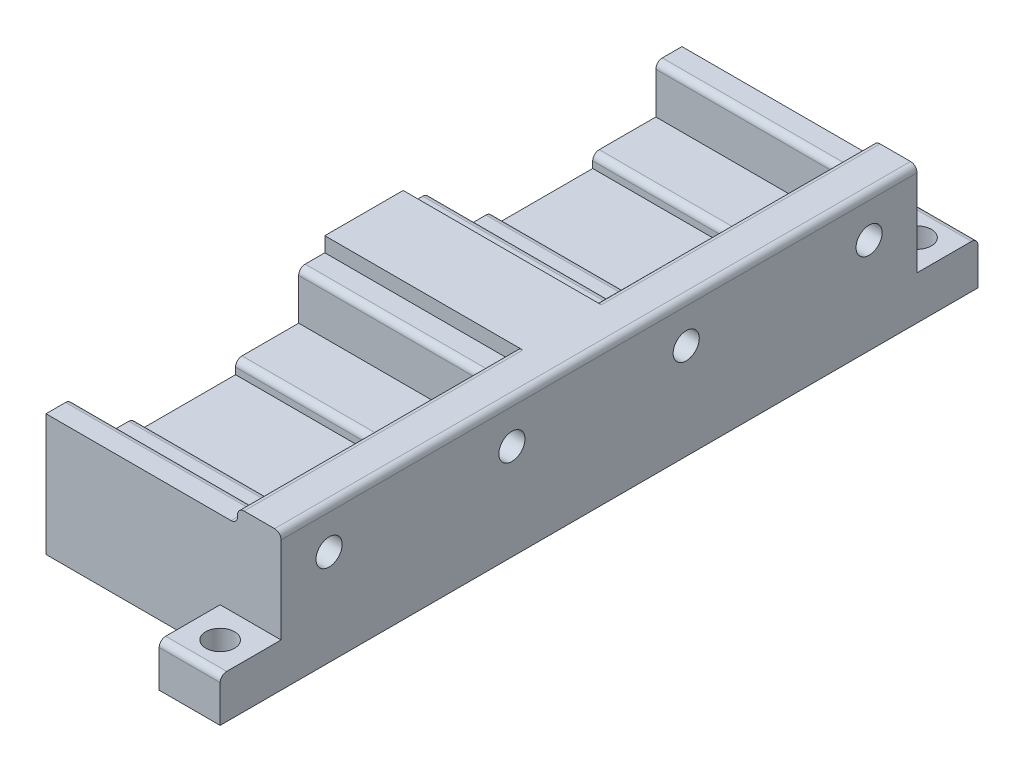
SolidWorks part; units mm, degrees
ref_plane "Front" through (0, 0, 0) normal (0, 0, 1) x (1, 0, 0)
ref_plane "Top" through (0, 0, 0) normal (0, 1, 0) x (1, 0, 0)
ref_plane "Right" through (0, 0, 0) normal (1, 0, 0) x (0, 0, -1)
sketch "Sketch1" plane through (0, 0, 0) normal (1, 0, 0) x (0, 0, -1)
  line L0 (-13.0089, 0) -> (13.0089, 0)
  line L1 (13.0089, 0) -> (13.0089, 8.5)
  line L2 (13.0089, 8.5) -> (5.7589, 8.5)
  line L3 (5.7589, 8.5) -> (5.7589, 7)
  line L4 (5.7589, 7) -> (-5.7589, 7)
  line L5 (-5.7589, 7) -> (-5.7589, 8.5)
  line L6 (-5.7589, 8.5) -> (-13.0089, 8.5)
  line L7 (-13.0089, 8.5) -> (-13.0089, 0)
  dimension "D1" = 8.5
  dimension "D2" = 7.25
  dimension "D3" = 26.0178
  dimension "D4" = 1.5
extrude "Boss-Extrude1" add sketch "Sketch1" along normal mid plane 22
sketch "Sketch3" plane through (0, 0, 0) normal (0, -1, 0) x (1, 0, 0)
  line L1 (-11, -13.0089) -> (11, -13.0089)
  line L2 (-11, -13.0089) -> (-11, -16.0089)
  line L3 (-11, -16.0089) -> (11, -16.0089)
  line L4 (11, -13.0089) -> (11, -16.0089)
  line L5 (-11, 13.0089) -> (11, 13.0089)
  line L6 (-11, 13.0089) -> (-11, 16.0089)
  line L7 (-11, 16.0089) -> (11, 16.0089)
  line L8 (11, 13.0089) -> (11, 16.0089)
  dimension "D1" = 3
  dimension "D2" = 22
  dimension "D3" = 3
  dimension "D4" = 22
extrude "Boss-Extrude2" add sketch "Sketch3" against normal blind 14
sketch "Sketch4" plane through (11, 0, 0) normal (1, 0, 0) x (0, 0, -1)
  line L0 (0, 0) -> (0, 15.7) construction
  line L1 (-16.0089, 0) -> (16.0089, 0) construction
  line L2 (-8.8, 15.7) -> (-16.0089, 15.7)
  line L3 (-16.0089, 14) -> (-16.0089, 0) construction
  line L4 (-16.0089, 15.7) -> (-16.0089, 0)
  line L5 (-16.0089, 0) -> (16.0089, 0)
  line L6 (16.0089, 0) -> (16.0089, 15.7)
  line L7 (16.0089, 14) -> (16.0089, 0) construction
  line L8 (16.0089, 15.7) -> (-8.8, 15.7)
  point P6 (0, 0)
  dimension "D2" = 15.7
extrude "Boss-Extrude3" add sketch "Sketch4" along normal blind 5
sketch "Sketch5" plane through (16, 0, 0) normal (1, 0, 0) x (0, 0, -1)
  line L0 (-16.0089, 11) -> (-10.5, 11) construction
  line L1 (-16.0089, 15.7) -> (-16.0089, 0) construction
  line L2 (-10.5, 11) -> (-10.5, 0) construction
  line L3 (-16.0089, 0) -> (16.0089, 0) construction
  line L4 (0, 0) -> (0, 15.7) construction
  line L5 (16.0089, 15.7) -> (-16.0089, 15.7) construction
  circle A0 centre (-10.5, 11) radius 1.5
  circle A1 centre (10.5, 11) radius 1.5
  point P13 (0, 0)
  dimension "D3" = 3
  dimension "D1" = 5.5089
  dimension "D2" = 11
extrude "Cut-Extrude1" cut sketch "Sketch5" against normal through all
sketch "Sketch6" plane through (0, 0, 0) normal (0, -1, 0) x (1, 0, 0)
  line L15 (16, 16.0089) -> (9, 16.0089)
  line L20 (16, 16.0089) -> (16, 23.0089)
  line L21 (16, 23.0089) -> (9, 23.0089)
  line L22 (9, 16.0089) -> (9, 23.0089)
  dimension "D3" = 7
  dimension "D4" = 7
extrude "Boss-Extrude4" add sketch "Sketch6" against normal blind 5
sketch "Sketch10" plane through (0, 0, 0) normal (0, -1, 0) x (1, 0, 0)
  line L0 (9, 19.5089) -> (16, 19.5089) construction
  line L1 (9, 23.0089) -> (9, 16.0089) construction
  line L2 (16, 23.0089) -> (16, -16.0089) construction
  line L3 (12.5, 23.0089) -> (12.5, 19.5089) construction
  line L4 (16, 23.0089) -> (9, 23.0089) construction
  circle A0 centre (12.5, 19.5089) radius 1.65
  dimension "D1" = 3.3
extrude "Cut-Extrude2" cut sketch "Sketch10" against normal through all
sketch "Sketch8" plane through (0, 0, -16.0089) normal (0, 0, -1) x (-1, 0, 0)
  line L1 (11, 0) -> (-16, 0)
  line L2 (11, 0) -> (11, 15.7)
  line L3 (11, 15.7) -> (-16, 15.7)
  line L4 (-16, 0) -> (-16, 15.7)
  point P6 (-16, 15.7)
extrude "Boss-Extrude5" add sketch "Sketch8" along normal blind 4.5
fillet "Fillet1" radius 0.75 11 edges at (12.5, 5, 23.0089) (0, 8.5, 5.7589) (0, 8.5, -5.7589) (11, 11.25, 13.0089) (11, 11.25, -13.0089) (0, 14, 13.0089) (0, 14, -13.0089) (11, 15.7, 0) (11, 14, 14.5089) (11, 14, -14.5089) (16, 15.7, -2.25)
mirror "Mirror6" about plane through (0, 0, -20.5089) normal (0, 0, -1) of bodies 133
